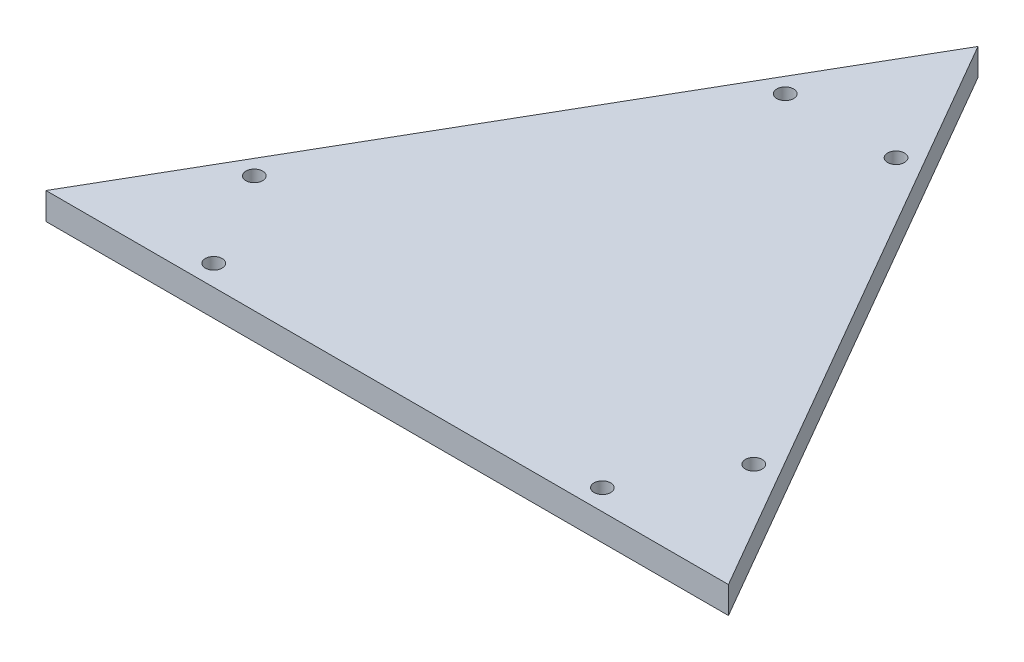
SolidWorks part; units mm, degrees
ref_plane "Alzado" through (0, 0, 0) normal (0, 0, 1) x (1, 0, 0)
ref_plane "Planta" through (0, 0, 0) normal (0, 1, 0) x (1, 0, 0)
ref_plane "Vista lateral" through (0, 0, 0) normal (1, 0, 0) x (0, 0, -1)
sketch "Croquis1" plane through (0, 0, 0) normal (0, 1, 0) x (1, 0, 0)
  line L14 (101.6025, 0) -> (0, 175.908)
  line L19 (-55, 0) -> (55, 0) construction
  line L20 (0, -55) -> (0, 55) construction
  line L22 (0, 175.908) -> (-101.6025, 0)
  line L23 (-101.6025, 0) -> (101.6025, 0)
  point P0 (0, 0)
extrude "Saliente-Extruir2" add sketch "Croquis1" along normal blind 8
sketch "Croquis3" plane through (0, 8, 0) normal (0, 1, 0) x (1, 0, 0)
  line L2 (0, -4.4) -> (0, 4.4) construction
  line L6 (-4.4, 0) -> (4.4, 0) construction
  circle A2 centre (-16.5, 135) radius 2.5
  circle A3 centre (16.5, 135) radius 2.5
  circle A4 centre (-57.8622, 6.201) radius 2.5
  circle A5 centre (-74.3622, 34.7798) radius 2.5
  circle A6 centre (57.8622, 6.201) radius 2.5
  circle A7 centre (74.3622, 34.7798) radius 2.5
  dimension "D3" = 5
  dimension "D4" = 5
  dimension "D10" = 5
  dimension "D11" = 5
  dimension "D13" = 5
  dimension "D14" = 5
  dimension "D1" = 33
  dimension "D5" = 16.5
  dimension "D6" = 33
  dimension "D7" = 33
  dimension "D8" = 34.7798
  dimension "D9" = 74.3622
  dimension "D18" = 135
  dimension "D19" = 74.3622
  dimension "D20" = 34.7798
extrude "Cortar-Extruir1" cut sketch "Croquis3" against normal blind 31
